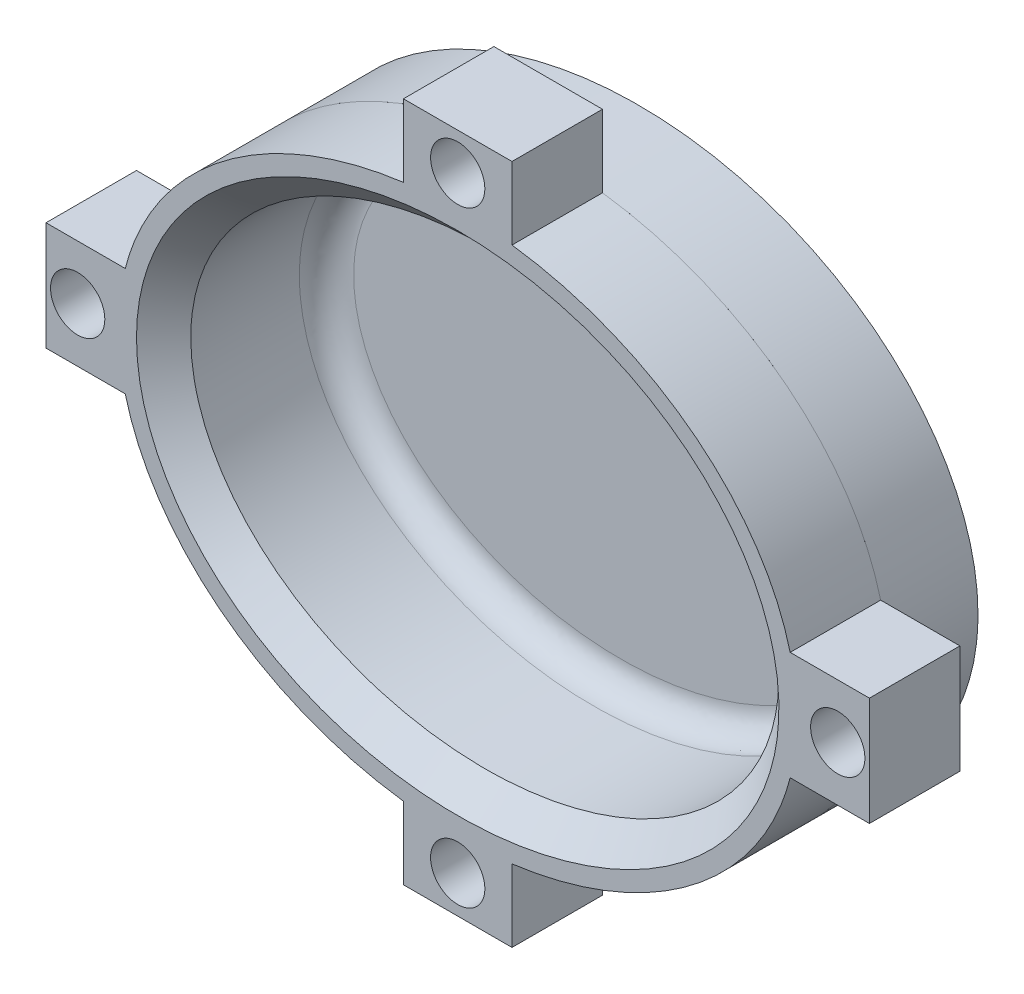
SolidWorks part; units mm, degrees
ref_plane "Alzado" through (0, 0, 0) normal (0, 0, 1) x (1, 0, 0)
ref_plane "Planta" through (0, 0, 0) normal (0, 1, 0) x (1, 0, 0)
ref_plane "Vista lateral" through (0, 0, 0) normal (1, 0, 0) x (0, 0, -1)
sketch "Sketch1" plane through (0, 0, 0) normal (0, 0, 1) x (1, 0, 0)
  line L0 (0, 40.4956) -> (0, 30) construction
  line L1 (-6, 29.6135) -> (-6, 37.6135)
  line L2 (-6, 37.6135) -> (0, 37.6135)
  line L3 (0, 37.6135) -> (6, 37.6135)
  line L4 (6, 37.6135) -> (6, 29.6135)
  line L5 (-37.5, 0) -> (37.5, 0) construction
  line L6 (6, -37.6135) -> (6, -29.6135)
  line L7 (0, -37.6135) -> (6, -37.6135)
  line L8 (-6, -37.6135) -> (0, -37.6135)
  line L9 (-6, -29.6135) -> (-6, -37.6135)
  line L10 (-37.5, 0) -> (-45.5, 0) construction
  line L11 (-36.7423, 6) -> (-45.5, 6)
  line L12 (-45.5, 6) -> (-45.5, -6)
  line L13 (-36.7423, -6) -> (-45.5, -6)
  line L14 (0, 0) -> (0, 15.1486) construction
  line L15 (36.7423, -6) -> (45.5, -6)
  line L16 (45.5, 6) -> (45.5, -6)
  line L17 (36.7423, 6) -> (45.5, 6)
  circle A0 centre (0, 33.5) radius 3
  circle A1 centre (0, -33.5) radius 3
  circle A2 centre (-42, 0) radius 3
  circle A3 centre (42, 0) radius 3
  ellipse E0 centre (0, 0) end of major axis (-37.5, 0) minor radius 30 (-6, 29.6135) -> (-36.7423, 6) ccw
  ellipse E1 centre (0, 0) end of major axis (-37.5, 0) minor radius 30 (6, -29.6135) -> (36.7423, -6) ccw
  ellipse E2 centre (0, 0) end of major axis (-37.5, 0) minor radius 30 (36.7423, 6) -> (6, 29.6135) ccw
  ellipse E3 centre (0, 0) end of major axis (-37.5, 0) minor radius 30 (-36.7423, -6) -> (-6, -29.6135) ccw
  point P9 (-6, 29.6135)
  point P10 (6, 29.6135)
  point P20 (-36.7423, 6)
  point P21 (-36.7423, -6)
  point P39 (36.7423, -6)
  point P41 (36.7423, 6)
  point P56 (0, 0)
  point P57 (0, 0)
  dimension "D6" = 6
  dimension "D11" = 6
  dimension "D13" = 67
  dimension "D1" = 30
  dimension "D2" = 37.5
  dimension "D3" = 6
  dimension "D4" = 6
  dimension "D5" = 8
  dimension "D7" = 3.5
  dimension "D8" = 8
  dimension "D9" = 6
  dimension "D10" = 6
  dimension "D12" = 4.5
extrude "Boss-Extrude1" add sketch "Sketch1" along normal blind 10
sketch "Sketch2" plane through (0, 0, 0) normal (0, 0, 1) x (1, 0, 0)
  ellipse E0 centre (0, 0) end of major axis (37.5, 0) minor radius 30.0005
  ellipse E1 centre (0, 0) end of major axis (32.5, 0) minor radius 25 construction
  dimension "D1" = 30.0005
  dimension "D2" = 37.5
  dimension "D3" = 25
  dimension "D4" = 32.5
extrude "Boss-Extrude2" add sketch "Sketch2" against normal blind 10
sketch "Sketch3" plane through (0, 0, 10) normal (0, 0, 1) x (1, 0, 0)
  ellipse E0 centre (0, 0) end of major axis (-32.5, 0) minor radius 25
  dimension "D1" = 25
extrude "Cut-Extrude1" cut sketch "Sketch3" against normal blind 18
fillet "Fillet1" radius 3 1 edges at (-32.5, 0, -8)
chamfer "Chamfer1" distance 3 angle 45 1 edges at (-32.5, 0, 10)
sketch "Sketch4" plane through (0, 0, 10) normal (0, 0, 1) x (1, 0, 0)
  ellipse E0 centre (0, 0) end of major axis (35.5, 0) minor radius 28 construction
  ellipse E1 centre (0, 0) end of major axis (37.5, 0) minor radius 30
  spline S0 degree 3 poles (-35.352, 3.1356) (-35.5735, 0.0092) (-35.3537, -3.121) (-34.7013, -6.1891) (-33.6379, -9.1461) (-32.201, -11.9439) (-30.4366, -14.5427) (-28.3898, -16.923) (-26.1051, -19.0734) (-23.6204, -20.9882) (-20.9745, -22.6643) (-18.2009, -24.1042) (-15.3142, -25.317) (-12.3412, -26.3027) (-9.3099, -27.063) (-6.2424, -27.6026) (-3.1404, -27.9269) (-0.0129, -28.0362) (3.1181, -27.9287) (6.2303, -27.6046) (9.3104, -27.0633) (12.3494, -26.3005) (15.3226, -25.3137) (18.2044, -24.1024) (20.9769, -22.663) (23.624, -20.9858) (26.1106, -19.0687) (28.4003, -16.9127) (30.4483, -14.5278) (32.2127, -11.9238) (33.6482, -9.1233) (34.7075, -6.1667) (35.3578, -3.0924) (35.5746, 0.0471) (35.3445, 3.1932) (34.6788, 6.2648) (33.6107, 9.2062) (32.1747, 11.9873) (30.4099, 14.5771) (28.3625, 16.9514) (26.0778, 19.0965) (23.5946, 21.0059) (20.9522, 22.6769) (18.1796, 24.1143) (15.2946, 25.3242) (12.3263, 26.3067) (9.3032, 27.0643) (6.2408, 27.6028) (3.1398, 27.927) (0.0152, 28.0361) (-3.1107, 27.929) (-6.2154, 27.6065) (-9.2917, 27.0672) (-12.3278, 26.3066) (-15.3006, 25.3219) (-18.1864, 24.1111) (-20.9672, 22.669) (-23.6153, 20.9917) (-26.0997, 19.0776) (-28.385, 16.9286) (-30.4308, 14.55) (-32.1966, 11.9506) (-33.632, 9.1599) (-34.6962, 6.2055) (-35.352, 3.1356) (-35.5735, 0.0092) (-35.3537, -3.121) knots -0.046899 -0.031286 -0.015668 0 0.015529 0.031207 0.046859 0.062487 0.078221 0.093825 0.109442 0.125163 0.140765 0.156322 0.171944 0.187642 0.203219 0.218739 0.234282 0.249923 0.265602 0.281196 0.296779 0.312431 0.328113 0.343683 0.359233 0.374875 0.390586 0.406219 0.421927 0.437603 0.45325 0.468968 0.484532 0.500197 0.515974 0.531649 0.547149 0.56274 0.578436 0.594008 0.609634 0.625322 0.640882 0.65643 0.672072 0.687718 0.703245 0.718739 0.734279 0.749934 0.76556 0.781116 0.796678 0.812327 0.827982 0.843567 0.85918 0.874873 0.890483 0.906113 0.921806 0.937408 0.953101 0.968714 0.984332 1 1.015529 1.031207 1.046859 only from (-35.5, 0) to (-35.5, 0) construction
  point P0 (0, 28)
  point P1 (35.5, 0)
  dimension "D1" = 30
  dimension "D2" = 37.5
